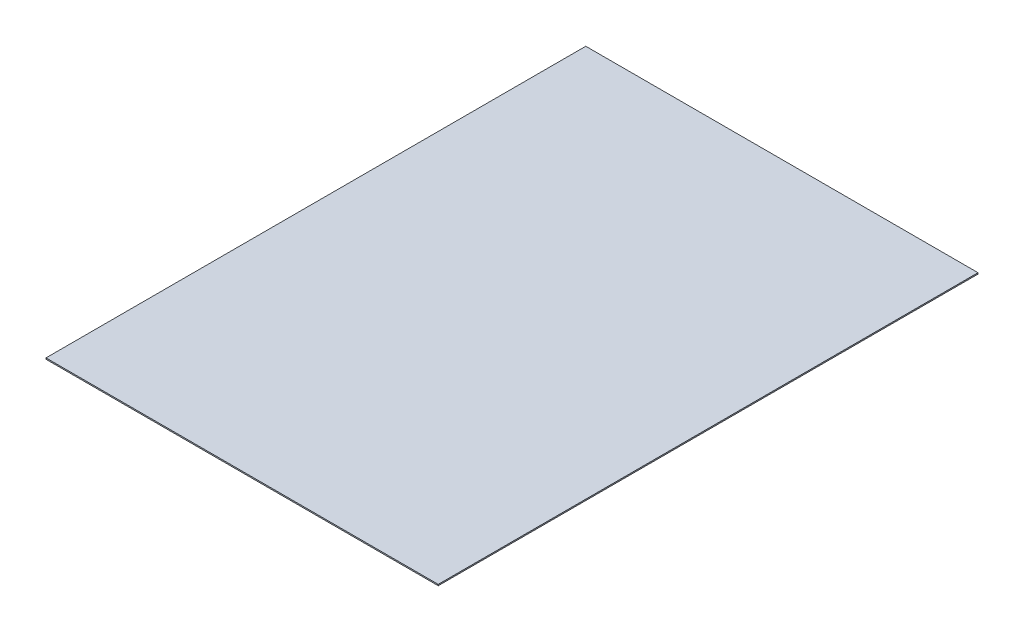
SolidWorks part; units mm, degrees
ref_plane "Alzado" through (0, 0, 0) normal (0, 0, 1) x (1, 0, 0)
ref_plane "Planta" through (0, 0, 0) normal (0, 1, 0) x (1, 0, 0)
ref_plane "Vista lateral" through (0, 0, 0) normal (1, 0, 0) x (0, 0, -1)
sketch "Croquis1" plane through (0, 0, 0) normal (0, 1, 0) x (1, 0, 0)
  line L1 (0, 0) -> (914.3, 0)
  line L2 (0, 0) -> (0, -1258.2)
  line L3 (0, -1258.2) -> (914.3, -1258.2)
  line L4 (914.3, 0) -> (914.3, -1258.2)
  dimension "D1" = 1258.2
  dimension "D2" = 914.3
extrude "Saliente-Extruir1" add sketch "Croquis1" along normal blind 2.9
